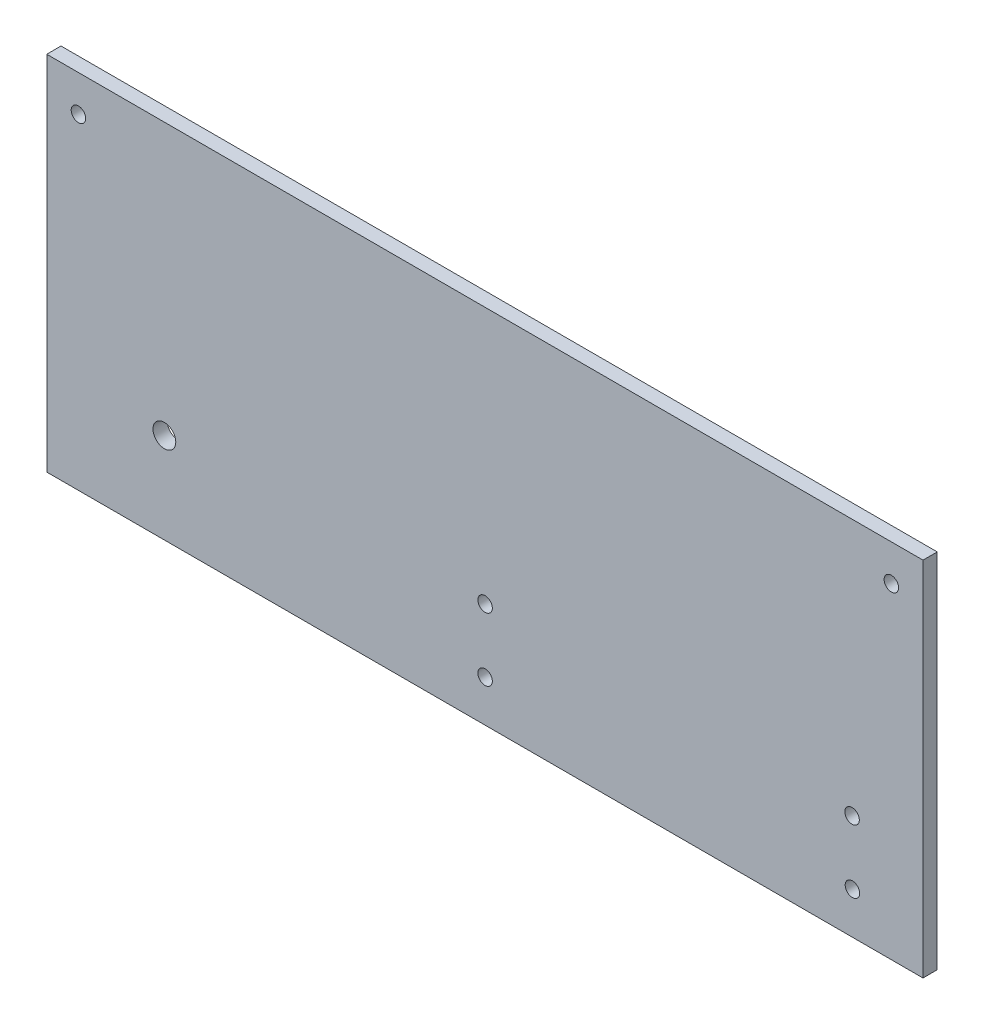
SolidWorks part; units mm, degrees
ref_plane "Front Plane" through (0, 0, 0) normal (0, 0, 1) x (1, 0, 0)
ref_plane "Top Plane" through (0, 0, 0) normal (0, 1, 0) x (1, 0, 0)
ref_plane "Right Plane" through (0, 0, 0) normal (1, 0, 0) x (0, 0, -1)
sketch "Sketch1" plane through (0, 0, 0) normal (0, 0, 1) x (1, 0, 0)
  line L5 (4, 101.6) -> (250, 101.6)
  line L6 (127.063, 3.048) -> (127.063, 0) construction
  line L22 (4, 91.44) -> (12.89, 91.44) construction
  line L23 (250, 101.6) -> (222.568, 101.6) construction
  line L32 (127, 101.6) -> (127, 0) construction
  line L35 (4, 0) -> (4, 101.6)
  line L36 (250, 0) -> (250, 101.6)
  line L52 (127.063, 3.048) -> (133.667, 3.048) construction
  line L53 (133.667, 3.048) -> (133.667, 39.116) construction
  line L54 (133.667, 39.116) -> (120.459, 39.116) construction
  line L55 (120.459, 39.116) -> (120.459, 3.048) construction
  line L56 (120.459, 3.048) -> (127.063, 3.048) construction
  line L57 (127.063, 39.116) -> (127.063, 29.464) construction
  line L58 (127.063, 29.464) -> (127.063, 11.684) construction
  line L59 (250, 0) -> (4, 0)
  circle A7 centre (127.063, 29.464) radius 2.032
  circle A8 centre (127.063, 11.684) radius 2.032
  circle A10 centre (37.02, 25.4) radius 3.2004
  circle A11 centre (230.0864, 29.464) radius 2.032
  circle A12 centre (230.188, 11.684) radius 2.032
  circle A13 centre (12.89, 91.44) radius 2.032
  circle A14 centre (241.11, 91.44) radius 2.032
  dimension "D1" = 246
  dimension "D5" = 33.02
  dimension "D8" = 8.89
  dimension "D9" = 10.16
  dimension "D27" = 4.064
  dimension "D4" = 19.812
  dimension "D3" = 19.9136
  dimension "D10" = 10.16
  dimension "D2" = 101.6
  dimension "D6" = 25.4
  dimension "D7" = 17.78
  dimension "D11" = 8.89
  dimension "D22" = 36.068
  dimension "D23" = 13.208
  dimension "D24" = 9.652
  dimension "D25" = 123.063
  dimension "D26" = 11.684
  dimension "D29" = 17.78
extrude "Boss-Extrude1" add sketch "Sketch1" along normal blind 4
